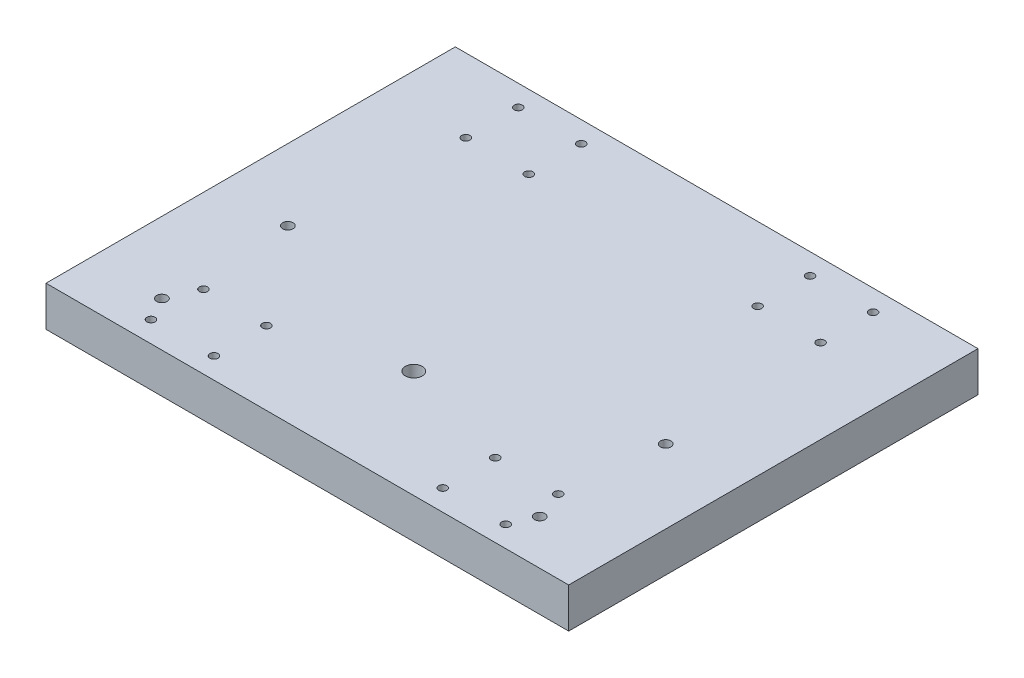
SolidWorks part; units mm, degrees
ref_plane "Front Plane" through (0, 0, 0) normal (0, 0, 1) x (1, 0, 0)
ref_plane "Top Plane" through (0, 0, 0) normal (0, 1, 0) x (1, 0, 0)
ref_plane "Right Plane" through (0, 0, 0) normal (1, 0, 0) x (0, 0, -1)
sketch "Sketch1" plane through (0, 0, 0) normal (0, 1, 0) x (1, 0, 0)
  line L1 (-70, -44.0508) -> (179, -44.0508)
  line L2 (-70, -44.0508) -> (-70, 150.9492)
  line L3 (-70, 150.9492) -> (179, 150.9492)
  line L4 (179, -44.0508) -> (179, 150.9492)
  circle A0 centre (-30, -9.0508) radius 1.95
  circle A1 centre (0, -9.0508) radius 1.95
  circle A2 centre (0, -34.0508) radius 1.95
  circle A3 centre (-30, -34.0508) radius 1.95
  circle A4 centre (109, -34.0508) radius 1.95
  circle A5 centre (109, -9.0508) radius 1.95
  circle A6 centre (139, -9.0508) radius 1.95
  circle A7 centre (139, -34.0508) radius 1.95
  circle A8 centre (109, 115.9492) radius 1.95
  circle A9 centre (109, 140.9492) radius 1.95
  circle A10 centre (139, 140.9492) radius 1.95
  circle A11 centre (139, 115.9492) radius 1.95
  circle A12 centre (-30, 115.9492) radius 1.95
  circle A13 centre (-30, 140.9492) radius 1.95
  circle A14 centre (0, 140.9492) radius 1.95
  circle A15 centre (0, 115.9492) radius 1.95
  point P37 (149.7853, 148.2588)
  point P38 (150.1895, 148.4356)
  point P39 (149, 149.4929)
  point P40 (149, 150.9492)
  point P41 (-228.5768, 86.8409)
  dimension "D1" = 3.9
  dimension "D2" = 3.9
  dimension "D3" = 3.9
  dimension "D4" = 3.9
  dimension "D6" = 30
  dimension "D10" = 10
  dimension "D13" = 10
  dimension "D14" = 139
  dimension "D15" = 150
  dimension "D5" = 25
  dimension "D7" = 115.9492
  dimension "D11" = 40
  dimension "D12" = 40
  dimension "D8" = 2
  dimension "D9" = 2
extrude "Boss-Extrude1" add sketch "Sketch1" along normal blind 19.05
sketch "Sketch2" plane through (0, 19.05, 0) normal (0, 1, 0) x (1, 0, 0)
  line L0 (-70, -44.0508) -> (179, -44.0508) construction
  point P0 (-36.0923, -22.7508)
  point P1 (-36.0923, 37.2492)
  point P2 (143.9077, 37.2492)
  point P3 (143.9077, -22.7508)
  point P4 (-18.7531, 76.5922)
  point P5 (0, 0)
  point P6 (0, 0)
  point P7 (0, 0)
  point P8 (0, 0)
  point P9 (123.4222, 80.7619)
  point P10 (0, 0)
  point P11 (-17.5036, 23.3827)
  point P12 (-15.4917, -21.6038)
  point P15 (-36.0923, -22.7508)
  point P16 (-15.5, -22.7508)
  dimension "D1" = 180
  dimension "D2" = 60
  dimension "D3" = 21.3
hole_wizard "M6x1.0 Tapped Hole1" positions "Sketch3" profile "Sketch4" tap size "M6x1.0" standard "ANSI Metric" end condition through all
sketch "Sketch3" plane through (0, 19.05, 0) normal (0, 1, 0) x (1, 0, 0)
  point P0 (-36.0923, 37.2492)
  point P3 (143.9077, 37.2492)
  point P6 (143.9077, -22.7508)
  point P9 (-36.0923, -22.7508)
sketch "Sketch4" plane through (-36.0923, 19.05, -37.2492) normal (1, 0, 0) x (0, 0, 1)
  line L0 (0, 0) -> (0, 19.05)
  line L1 (0, 19.05) -> (2.5, 19.05)
  line L2 (2.5, 19.05) -> (2.5, 0)
  line L5 (2.5, 0) -> (0, 0)
  line L11 (0, -6.35) -> (0, 107.95) construction
  dimension "Thru Tap Drill Dia." = 5
  dimension "Thru Tap Drill Depth" = 19.05
sketch "Sketch5" plane through (0, 19.05, 0) normal (0, 1, 0) x (1, 0, 0)
  line L0 (-36.0923, 37.2492) -> (143.9077, -22.7508) construction
  line L1 (143.9077, 37.2492) -> (-36.0923, -22.7508) construction
  point P12 (53.9077, 7.2492)
  dimension "D1" = 189.7367
  dimension "D2" = 189.7367
hole_wizard "Ø8.0mm Dowel Hole1" positions "Sketch6" profile "Sketch7" hole size "Ø8.0" standard "ANSI Metric" end condition through all
sketch "Sketch6" plane through (0, 19.05, 0) normal (0, 1, 0) x (1, 0, 0)
  point P0 (53.9077, 7.2492)
sketch "Sketch7" plane through (53.9077, 19.05, -7.2492) normal (1, 0, 0) x (0, 0, 1)
  line L0 (0, 0) -> (0, 19.05)
  line L1 (0, 19.05) -> (4, 19.05)
  line L2 (4, 19.05) -> (4, 0)
  line L5 (4, 0) -> (0, 0)
  line L11 (0, -6.35) -> (0, 107.95) construction
  dimension "Thru Hole Dia." = 8
  dimension "Thru Hole Depth" = 19.05
